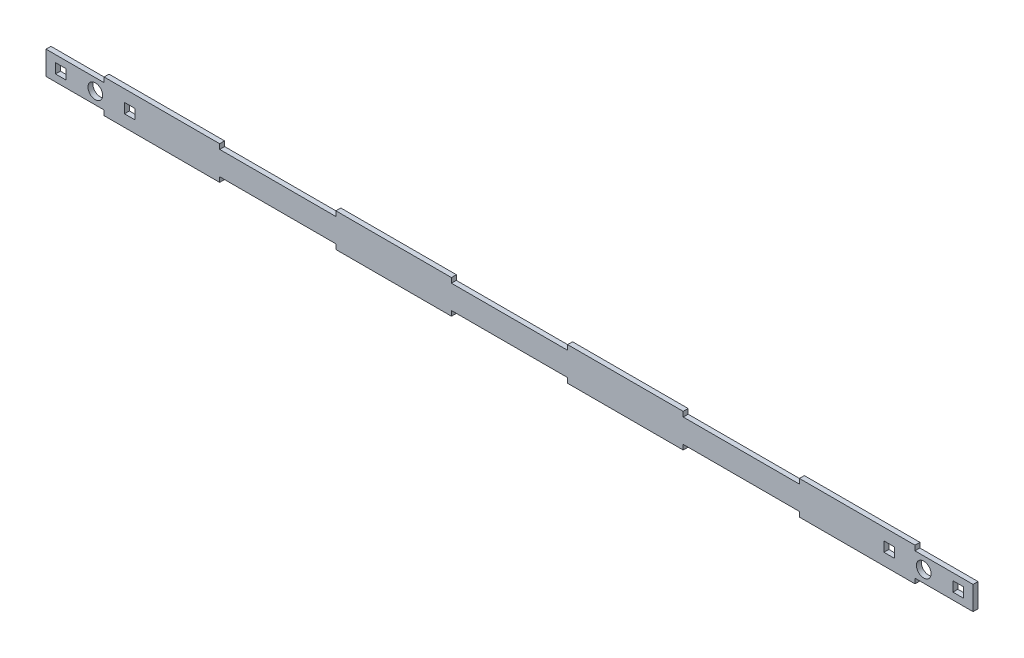
SolidWorks part; units mm, degrees
material "Acrylique (impact moyen-haut)"
ref_plane "Plan de face" through (0, 0, 0) normal (0, 0, 1) x (1, 0, 0)
ref_plane "Plan de dessus" through (0, 0, 0) normal (0, 1, 0) x (1, 0, 0)
ref_plane "Plan de droite" through (0, 0, 0) normal (1, 0, 0) x (0, 0, -1)
sketch "Esquisse1" plane through (0, 0, 0) normal (0, 0, 1) x (1, 0, 0)
  line L1 (-298.45, -10.795) -> (298.45, -10.795)
  line L2 (-298.45, -10.795) -> (-298.45, 10.795)
  line L3 (-298.45, 10.795) -> (298.45, 10.795)
  line L4 (298.45, -10.795) -> (298.45, 10.795)
  line L5 (-298.45, -10.795) -> (298.45, 10.795) construction
  line L6 (-298.45, 10.795) -> (298.45, -10.795) construction
  point P0 (0, 0)
  dimension "D1" = 21.59
  dimension "D2" = 596.9
extrude "Boss.-Extru.1" add sketch "Esquisse1" along normal blind 3.175
sketch "Esquisse4" plane through (0, 0, 3.175) normal (0, 0, 1) x (1, 0, 0)
  line L0 (298.45, 10.795) -> (-298.45, 10.795) construction
  line L1 (-37.4063, 7.615) -> (37.4062, 7.615)
  line L2 (-37.4063, 7.615) -> (-37.4063, 10.795)
  line L3 (-37.4063, 10.795) -> (37.4062, 10.795)
  line L4 (37.4062, 7.615) -> (37.4062, 10.795)
  line L5 (-37.4063, 7.615) -> (37.4062, 10.795) construction
  line L6 (-37.4063, 10.795) -> (37.4062, 7.615) construction
  line L7 (-298.45, 10.795) -> (-298.45, -10.795) construction
  line L8 (-111.8188, 7.62) -> (-186.6313, 7.62)
  line L9 (-111.8188, 7.62) -> (-111.8188, 10.795)
  line L10 (-111.8188, 10.795) -> (-186.6313, 10.795)
  line L11 (-186.6313, 7.62) -> (-186.6313, 10.795)
  line L12 (-111.8188, 7.62) -> (-186.6313, 10.795) construction
  line L13 (-111.8188, 10.795) -> (-186.6313, 7.62) construction
  line L14 (-298.45, 10.795) -> (-261.0438, 10.795)
  line L15 (-298.45, 10.795) -> (-298.45, 7.62)
  line L16 (-298.45, 7.62) -> (-261.0438, 7.62)
  line L17 (-261.0438, 10.795) -> (-261.0438, 7.62)
  line L18 (0, -1.7463) -> (0, 1.7463) construction
  line L19 (111.8188, 10.795) -> (186.6313, 7.62) construction
  line L20 (111.8188, 7.62) -> (186.6313, 10.795) construction
  line L21 (261.0438, 10.795) -> (261.0438, 7.62)
  line L22 (298.45, 7.62) -> (261.0438, 7.62)
  line L23 (298.45, 10.795) -> (298.45, 7.62)
  line L24 (298.45, 10.795) -> (261.0438, 10.795)
  line L25 (186.6313, 7.62) -> (186.6313, 10.795)
  line L26 (111.8188, 10.795) -> (186.6313, 10.795)
  line L27 (111.8188, 7.62) -> (111.8188, 10.795)
  line L28 (111.8188, 7.62) -> (186.6313, 7.62)
  point P0 (0, 9.205)
  point P9 (-149.225, 9.2075)
  point P19 (-37.4063, 9.205)
  point P30 (149.225, 9.2075)
  dimension "D2" = 3.18
  dimension "D5" = 3.175
  dimension "D1" = 74.8125
  dimension "D4" = 74.4125
  dimension "D3" = 74.4125
  dimension "D6" = 3.175
extrude "Enlèv. mat.-Extru.3" cut sketch "Esquisse4" against normal through all
mirror "Symétrie3" about plane through (0, 0, 0) normal (0, 1, 0) of "Enlèv. mat.-Extru.3"
sketch "Esquisse5" plane through (0, 0, 3.175) normal (0, 0, 1) x (1, 0, 0)
  line L0 (-298.45, 7.62) -> (-298.45, -7.62) construction
  line L1 (-247.904, -3.175) -> (-241.046, -3.175)
  line L2 (-247.904, -3.175) -> (-247.904, 3.175)
  line L3 (-247.904, 3.175) -> (-241.046, 3.175)
  line L4 (-241.046, -3.175) -> (-241.046, 3.175)
  line L5 (-247.904, -3.175) -> (-241.046, 3.175) construction
  line L6 (-247.904, 3.175) -> (-241.046, -3.175) construction
  line L7 (-285.496, -3.175) -> (-292.354, -3.175)
  line L8 (-285.496, -3.175) -> (-285.496, 3.175)
  line L9 (-285.496, 3.175) -> (-292.354, 3.175)
  line L10 (-292.354, -3.175) -> (-292.354, 3.175)
  line L11 (-285.496, -3.175) -> (-292.354, 3.175) construction
  line L12 (-285.496, 3.175) -> (-292.354, -3.175) construction
  circle A0 centre (-266.7, 0) radius 4.7244
  point P2 (-244.475, 0)
  point P7 (-288.925, 0)
  point P12 (0, 0)
  point P13 (0, 0)
  point P15 (-249.0307, 0)
  point P16 (-286.8164, -1.4836)
  point P19 (-298.45, 0)
  point P20 (0, 0)
  point P21 (0, 0)
  dimension "D1" = 6.35
  dimension "D3" = 9.4488
  dimension "D2" = 6.858
  dimension "D4" = 266.7
  dimension "D5" = 22.225
  dimension "D6" = 22.225
extrude "Enlèv. mat.-Extru.4" cut sketch "Esquisse5" against normal through all
mirror "Symétrie4" about plane through (0, 0, 0) normal (1, 0, 0) of "Enlèv. mat.-Extru.4"
equation "\"encoche\"=74.6125"
equation "\"thickness_sheet\"=3.175"
equation "\"D5@Esquisse4\"=\"thickness_sheet\""
equation "\"D1@Esquisse4\"=\"encoche\"+0.2"
equation "\"D4@Esquisse4\"=\"encoche\"-0.2"
equation "\"D3@Esquisse4\"=\"encoche\"-0.2"
equation "\"D6@Esquisse4\"=\"thickness_sheet\""
